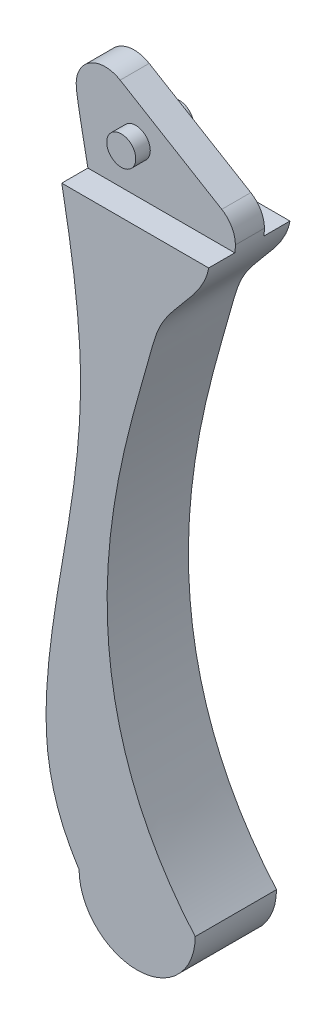
SolidWorks part; units mm, degrees
ref_plane "Front Plane" through (0, 0, 0) normal (0, 0, 1) x (1, 0, 0)
ref_plane "Top Plane" through (0, 0, 0) normal (0, 1, 0) x (1, 0, 0)
ref_plane "Right Plane" through (0, 0, 0) normal (1, 0, 0) x (0, 0, -1)
sketch "Sketch1" plane through (0, 0, 0) normal (0, 0, 1) x (1, 0, 0)
  line L0 (0, -225) -> (40, -225)
  line L2 (5.1531, 8.5701) -> (40.1531, -12.475)
  arc A1 (44.8377, -20.7582) -> (40.1531, -12.475) centre (35.1725, -20.7582) ccw
  arc A2 (5.1531, 8.5701) -> (-10, 0) centre (0, 0) ccw
  spline S0 degree 3 poles (-10, 0) (-10, -6.0336) (-1.9352, -36.5678) (2.9306, -106.9091) (-14.4969, -160.9447) (-10.7784, -208.4088) (0, -225) knots 0 0 0 0 0.308475 0.388558 0.80083 1 1 1 1
  spline S1 degree 3 poles (44.8377, -20.7582) (44.8377, -31.3694) (28.8894, -41.7829) (19.0268, -81.3215) (-10.38, -166.8625) (40, -225) knots 0 0 0 0 0.243335 0.343335 1 1 1 1
  dimension "D1" = 20
  dimension "D3" = 40
  dimension "D4" = 35
extrude "Boss-Extrude1" add sketch "Sketch1" along normal blind 28
sketch "Sketch4" plane through (0, -225, 0) normal (0, -1, 0) x (1, 0, 0)
  line L0 (20, 28) -> (20, 0)
  line L1 (0, 28) -> (40, 28) construction
  line L2 (0, 0) -> (40, 0) construction
  line L3 (20, 0) -> (40, 0)
  line L4 (40, 0) -> (40, 28)
  line L5 (40, 28) -> (20, 28)
revolve "Revolve2" add sketch "Sketch4" angle 180 about L0
ref_plane "Plane1" through (0, 0, 14) normal (0, 0, 1) x (1, 0, 0)
sketch "Sketch8" plane through (0, 0, 0) normal (1, 0, 0) x (0, 0, -1)
  line L1 (-28, 10) -> (-19, 10)
  line L2 (-28, 10) -> (-28, -23.213)
  line L3 (-28, -23.213) -> (-19, -23.213)
  line L4 (-19, 10) -> (-19, -23.213)
  dimension "D1" = 9
extrude "Cut-Extrude1" cut sketch "Sketch8" along normal mid plane 90
mirror "Mirror1" about plane through (0, 0, 14) normal (0, 0, 1) of "Cut-Extrude1"
sketch "Sketch9" plane through (0, 0, 19) normal (0, 0, 1) x (1, 0, 0)
  circle A0 centre (10.5251, -7.2453) radius 5
  dimension "D1" = 10
extrude "Boss-Extrude2" add sketch "Sketch9" along normal blind 5
mirror "Mirror2" about plane through (0, 0, 14) normal (0, 0, 1) of "Boss-Extrude2"
